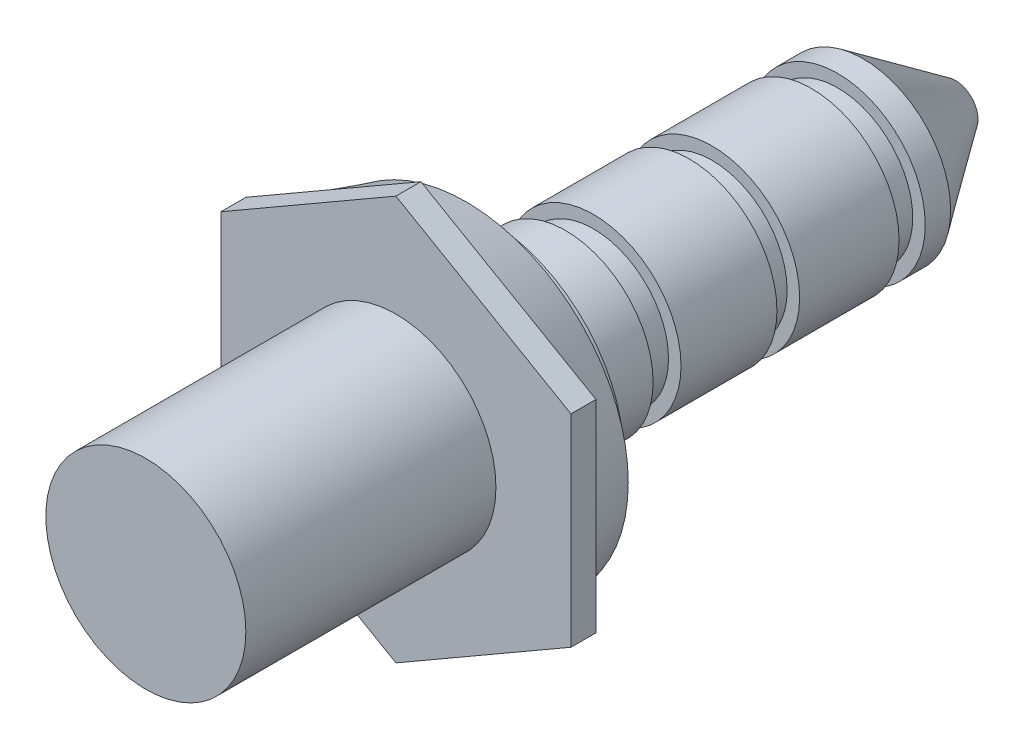
SolidWorks part; units mm, degrees
material "Acero al carbono no aleado"
ref_plane "Alzado" through (0, 0, 0) normal (0, 0, 1) x (1, 0, 0)
ref_plane "Planta" through (0, 0, 0) normal (0, 1, 0) x (1, 0, 0)
ref_plane "Vista lateral" through (0, 0, 0) normal (1, 0, 0) x (0, 0, -1)
sketch "Croquis1" plane through (0, 0, 0) normal (0, 0, 1) x (1, 0, 0)
  line L1 (0, -8.0829) -> (7, -4.0415)
  line L2 (7, -4.0415) -> (7, 4.0415)
  line L3 (7, 4.0415) -> (0, 8.0829)
  line L4 (0, 8.0829) -> (-7, 4.0415)
  line L5 (-7, 4.0415) -> (-7, -4.0415)
  line L6 (-7, -4.0415) -> (0, -8.0829)
  circle A0 centre (0, 0) radius 7 construction
  dimension "D1" = 14
extrude "Saliente-Extruir1" add sketch "Croquis1" along normal blind 1
sketch "Croquis2" plane through (0, 0, 1) normal (0, 0, 1) x (1, 0, 0)
  circle A0 centre (0, 0) radius 4
  dimension "D1" = 8
extrude "Saliente-Extruir2" add sketch "Croquis2" along normal blind 10
sketch "Croquis3" plane through (0, 0, 0) normal (0, 1, 0) x (1, 0, 0)
  line L0 (0, 21.3821) -> (0.8945, 21.3821)
  line L1 (0.8945, 21.3821) -> (3.5, 17.6825)
  line L2 (3.5, 17.6825) -> (3.5, 16.6668)
  line L3 (3.5, 16.6668) -> (3, 16.6668)
  line L4 (3, 16.6668) -> (3, 15.6205)
  line L5 (3, 15.6205) -> (3.5, 15.6205)
  line L6 (3.5, 15.6205) -> (3.5, 11.6443)
  line L7 (3.5, 11.6443) -> (3, 11.6443)
  line L8 (3, 11.6443) -> (3, 10.7374)
  line L9 (3, 10.7374) -> (3.5, 10.7374)
  line L10 (3.5, 10.7374) -> (3.5, 6.9007)
  line L11 (3.5, 6.9007) -> (3, 6.9007)
  line L12 (3, 6.9007) -> (3, 5.7846)
  line L13 (3, 5.7846) -> (3.5, 5.7846)
  line L14 (3.5, 5.7846) -> (3.5, 2.6455)
  line L15 (3.5, 2.6455) -> (5.4674, 2.6455)
  line L16 (5.4674, 2.6455) -> (5.4674, 1.8084)
  line L17 (5.4674, 1.8084) -> (6.4831, 1.8084)
  line L18 (6.4831, 1.8084) -> (7, 0)
  line L19 (7, 0) -> (0, 0)
  line L20 (0, 0) -> (0, 21.3821)
  dimension "D1" = 3.5
  dimension "D2" = 3
revolve "Revolución1" add sketch "Croquis3" angle 360 about L20
